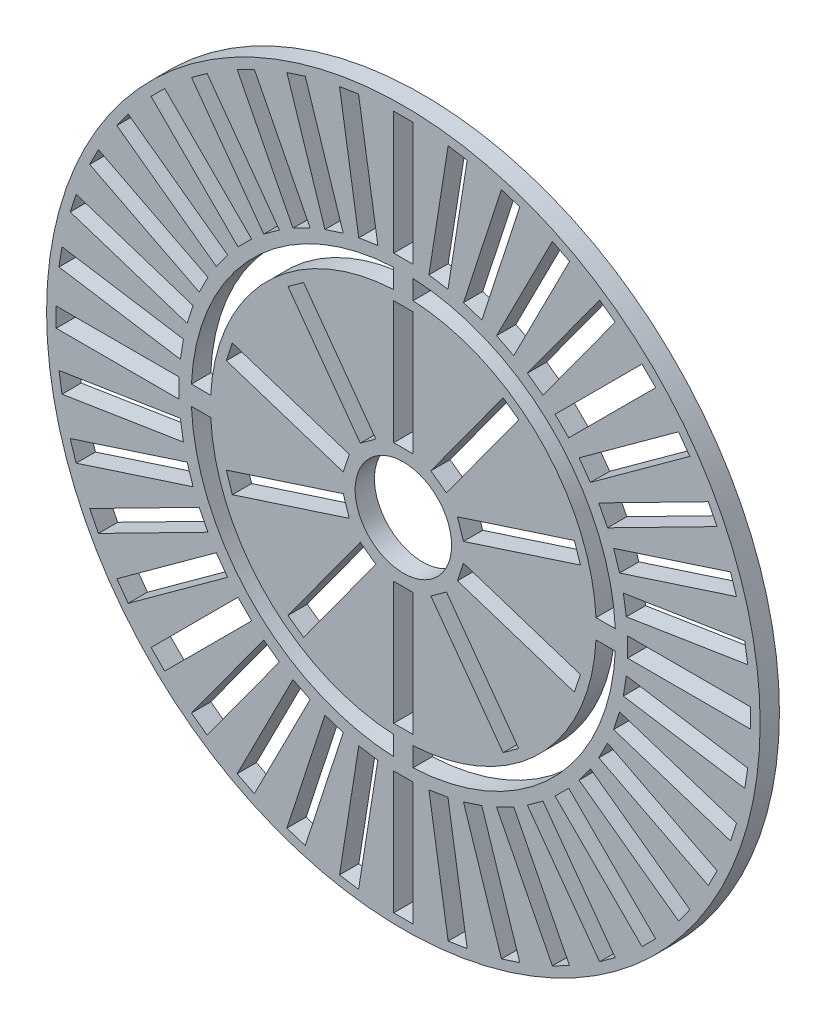
SolidWorks part; units mm, degrees
ref_plane "Front Plane" through (0, 0, 0) normal (0, 0, 1) x (1, 0, 0)
ref_plane "Top Plane" through (0, 0, 0) normal (0, 1, 0) x (1, 0, 0)
ref_plane "Right Plane" through (0, 0, 0) normal (1, 0, 0) x (0, 0, -1)
sketch "Sketch1" plane through (0, 0, 0) normal (0, 0, 1) x (1, 0, 0)
  line L0 (0, 20) -> (0, 22) construction
  line L1 (1, 21.9773) -> (1, 19.975)
  line L2 (-1, 21.9773) -> (-1, 19.975)
  line L3 (-1, 21) -> (1, 21) construction
  line L4 (21.9773, -1) -> (19.975, -1)
  line L5 (21.9773, 1) -> (19.975, 1)
  line L6 (-1, -21.9773) -> (-1, -19.975)
  line L7 (1, -21.9773) -> (1, -19.975)
  line L8 (-21.9773, 1) -> (-19.975, 1)
  line L9 (-21.9773, -1) -> (-19.975, -1)
  circle A0 centre (0, 0) radius 37
  arc A1 (-21.9773, -1) -> (-1, -21.9773) centre (0, 0) ccw
  arc A2 (-19.975, -1) -> (-1, -19.975) centre (0, 0) ccw
  circle A3 centre (0, 0) radius 5
  arc A4 (-21.9773, 1) -> (-21.9773, -1) centre (0, 0) ccw construction
  arc A5 (-19.975, 1) -> (-19.975, -1) centre (0, 0) ccw construction
  arc A6 (1, 21.9773) -> (0, 22) centre (0, 0) ccw construction
  arc A7 (-1, 21.9773) -> (-21.9773, 1) centre (0, 0) ccw
  arc A8 (0, 22) -> (-1, 21.9773) centre (0, 0) ccw construction
  arc A9 (0, 20) -> (-1, 19.975) centre (0, 0) ccw construction
  arc A10 (-1, 19.975) -> (-19.975, 1) centre (0, 0) ccw
  arc A11 (1, 19.975) -> (0, 20) centre (0, 0) ccw construction
  arc A12 (21.9773, -1) -> (21.9773, 1) centre (0, 0) ccw construction
  arc A13 (21.9773, 1) -> (1, 21.9773) centre (0, 0) ccw
  arc A14 (19.975, -1) -> (19.975, 1) centre (0, 0) ccw construction
  arc A15 (19.975, 1) -> (1, 19.975) centre (0, 0) ccw
  arc A16 (-1, -21.9773) -> (1, -21.9773) centre (0, 0) ccw construction
  arc A17 (1, -21.9773) -> (21.9773, -1) centre (0, 0) ccw
  arc A18 (-1, -19.975) -> (1, -19.975) centre (0, 0) ccw construction
  arc A19 (1, -19.975) -> (19.975, -1) centre (0, 0) ccw
  point P15 (0, 21)
  point P30 (0, 0)
  dimension "D1" = 74
  dimension "D2" = 15
  dimension "D3" = 2
  dimension "D4" = 15
  dimension "D5" = 2
  dimension "D6" = 4
extrude "Base" add sketch "Sketch1" along normal mid plane 2
sketch "Sketch2" plane through (0, 0, 1) normal (0, 0, 1) x (1, 0, 0)
  line L0 (0, 36) -> (0, 37) construction
  line L1 (-1, 36) -> (1, 36)
  line L2 (-1, 36) -> (-1, 23.25)
  line L3 (-1, 23.25) -> (1, 23.25)
  line L4 (1, 36) -> (1, 23.25)
  circle A0 centre (0, 0) radius 37 construction
  point P4 (0, 23.25)
  dimension "D1" = 2
  dimension "D2" = 1
  dimension "D3" = 12.75
extrude "Ytre ring" cut sketch "Sketch2" against normal blind 2
pattern_circular "CirPattern1" count 40 over 360 about axis through (0, 0, 0) along (0, 0, 1) of "Ytre ring"
sketch "Sketch3" plane through (0, 0, 1) normal (0, 0, 1) x (1, 0, 0)
  line L1 (-1, 18.975) -> (1, 18.975)
  line L2 (-1, 18.975) -> (-1, 6.225)
  line L3 (-1, 6.225) -> (1, 6.225)
  line L4 (1, 18.975) -> (1, 6.225)
  point P4 (0, 6.225)
  dimension "D1" = 2
  dimension "D2" = 12.75
  dimension "D3" = 1
extrude "Cut-Extrude2" cut sketch "Sketch3" against normal blind 2
pattern_circular "CirPattern2" count 10 over 360 about axis through (0, 0, 0) along (0, 0, 1) of "Cut-Extrude2"
